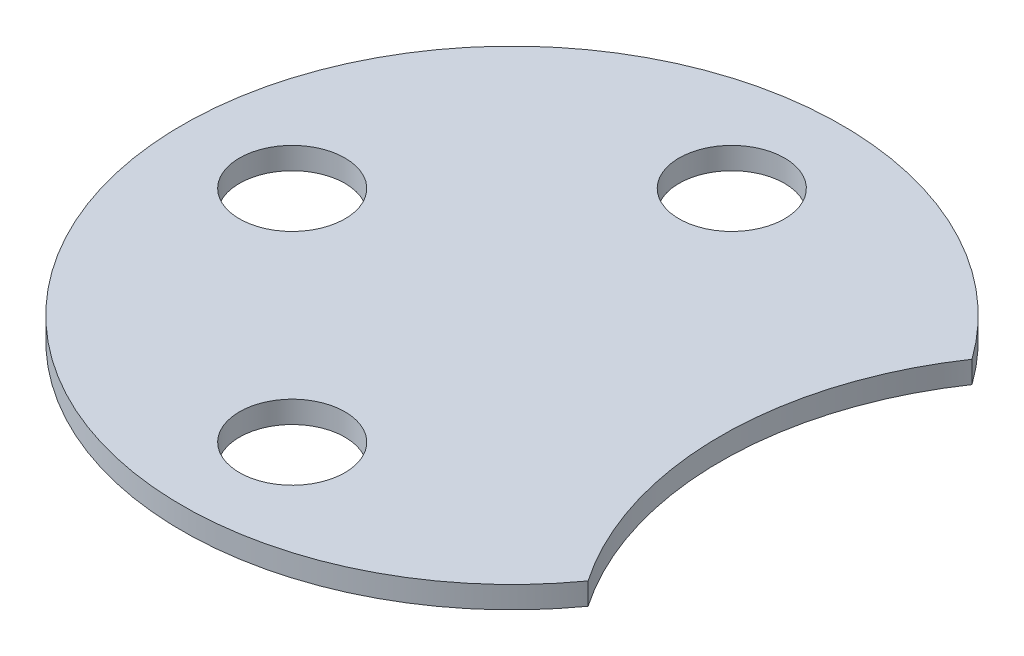
SolidWorks part; units mm, degrees
ref_plane "前视基准面" through (0, 0, 0) normal (0, 0, 1) x (1, 0, 0)
ref_plane "上视基准面" through (0, 0, 0) normal (0, 1, 0) x (1, 0, 0)
ref_plane "右视基准面" through (0, 0, 0) normal (1, 0, 0) x (0, 0, -1)
sketch "草图1" plane through (0, 0, 0) normal (0, 1, 0) x (1, 0, 0)
  circle A0 centre (0, 0) radius 75
  dimension "D1" = 150
extrude "凸台-拉伸1" add sketch "草图1" along normal blind 5
sketch "草图2" plane through (0, 0, 0) normal (0, -1, 0) x (1, 0, 0)
  circle A0 centre (0, 0) radius 50 construction
  point P3 (50, 0)
  point P7 (0, -50)
  point P8 (-50, 0)
  point P9 (0, 50)
  dimension "D1" = 100
  dimension "D2" = 4
hole_wizard "孔1" positions "草图2" profile "草图3" legacy
sketch "草图3" plane through (0, 0, 50) normal (1, 0, 0) x (0, 0, -1)
  line L0 (0, 0) -> (0, 5)
  line L1 (0, 5) -> (12, 5)
  line L2 (12, 5) -> (12, 0)
  line L3 (12, 0) -> (0, 0)
  line L4 (0, 110) -> (0, -10) construction
  dimension "直径" = 24
  dimension "深度" = 5
sketch "草图4" plane through (0, 0, 0) normal (0, -1, 0) x (1, 0, 0)
  circle A0 centre (125, 0) radius 77.5
  point P2 (0, 0)
  dimension "D1" = 155
  dimension "D2" = 125
extrude "切除-拉伸1" cut sketch "草图4" against normal blind 5
